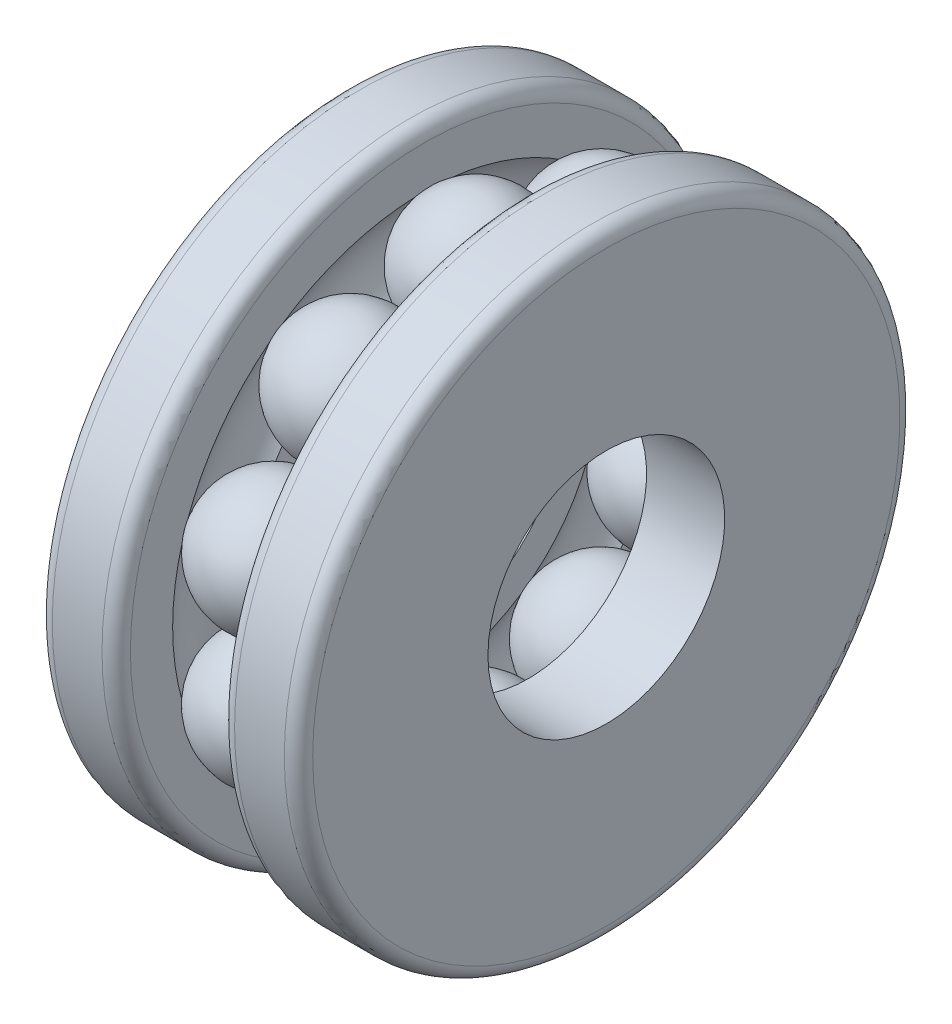
SolidWorks part; units mm, degrees
ref_plane "Front" through (0, 0, 0) normal (0, 0, 1) x (1, 0, 0)
ref_plane "Top" through (0, 0, 0) normal (0, 1, 0) x (1, 0, 0)
ref_plane "Right" through (0, 0, 0) normal (1, 0, 0) x (0, 0, -1)
sketch "Sketch1" plane through (0, 0, 0) normal (0, 0, 1) x (0, 1, 0)
  line L0 (0, 1.4099) -> (0, -1.5142) construction
  line L1 (6.25, 0) -> (11.75, 0)
  line L2 (4.3776, 0) -> (11.8663, 0) construction
  line L3 (9, 5.5) -> (13.0112, 5.5) construction
  line L4 (9, -5.5) -> (13.0112, -5.5) construction
  line L5 (5, 0) -> (5, 2.3607) construction
  line L6 (-5, 0) -> (-5, 2.3607) construction
  line L7 (13, 0) -> (13, 3.0588) construction
  line L8 (-13, 0) -> (-13, 3.0588) construction
  arc A0 (6.25, 0) -> (11.75, 0) centre (9, 0) ccw
  dimension "d0" = 5.5
  dimension "dd0" = 18
  dimension "T" = 11
  dimension "d" = 10
  dimension "DD" = 26
revolve "Revolve1" add sketch "Sketch1" angle 360 about L2
sketch "Sketch2" plane through (0, 0, 0) normal (0, 0, 1) x (0, 1, 0)
  line L0 (6, 5.5) -> (6, 2.2)
  line L1 (6, 2.2) -> (7.3836, 2.2)
  line L2 (6, 5.5) -> (13, 5.5)
  line L3 (13, 5.5) -> (13, 2.2)
  line L4 (13, 2.2) -> (10.6164, 2.2)
  line L5 (0, 4.8736) -> (0, -4.1797) construction
  line L6 (-8.0647, 0) -> (13.4529, 0) construction
  arc A0 (10.6164, 2.2) -> (7.3836, 2.2) centre (9, 0) ccw
  circle A1 centre (9, 0) radius 2.75 construction
  dimension "T" = 11
  dimension "dd1" = 5.46
  dimension "D" = 26
  dimension "d1" = 12
  dimension "B1/2" = 2.2
revolve "Revolve2" add sketch "Sketch2" angle 360 about L5
sketch "Sketch3" plane through (0, 0, 0) normal (0, 0, 1) x (0, 1, 0)
  line L0 (-2.5215, 0) -> (12.4263, 0) construction
  line L1 (5, -2.2) -> (7.3836, -2.2)
  line L2 (5, -2.2) -> (5, -5.5)
  line L3 (5, -5.5) -> (13, -5.5)
  line L4 (13, -2.2) -> (13, -5.5)
  line L5 (0, 8.7259) -> (0, -4.9884) construction
  line L6 (10.6164, -2.2) -> (13, -2.2)
  arc A0 (7.35, 2.2) -> (10.65, 2.2) centre (9, 0) ccw construction
  arc A1 (7.3836, -2.2) -> (10.6164, -2.2) centre (9, 0) ccw
  dimension "T" = 11
  dimension "d" = 10
  dimension "D1" = 5.46
  dimension "DD1" = 26
  dimension "D2" = 2.2
revolve "Revolve3" add sketch "Sketch3" angle 360 about L5
pattern_circular "Circular-Pattern1" count 10 over 360 about axis through (0, 0, 0) along (1, 0, 0) of "Revolve1"
fillet "Fillet1" radius 0.6 4 edges at (5.5, 0, 13) (2.2, 0, 13) (-2.2, 0, 13) (-5.5, 0, 13)
equation "\"d0@Sketch1\" = \"T@Sketch1\" / 2"
equation "\"dd0@Sketch1\" =  ( \"d@Sketch1\" + \"DD@Sketch1\" )  / 2"
equation "\"D@Sketch2\" = \"DD@Sketch1\""
equation "\"T@Sketch2\" = \"T@Sketch1\""
equation "\"dd1@Sketch2\" = \"d0@Sketch1\" - 0.04"
equation "\"B1/2@Sketch2\" = \"T@Sketch2\" / 5"
equation "\"d@Sketch3\" = \"d@Sketch1\""
equation "\"D2@Sketch3\" = \"B1/2@Sketch2\""
equation "\"D1@Sketch3\" = \"dd1@Sketch2\""
equation "\"T@Sketch3\" = \"T@Sketch2\""
equation "\"m@Circular-Pattern1\" = int( 3.14159265 / atn((  \"d0@Sketch1\"/ 2) / sqr( \"dd0@Sketch1\"/2 * \"dd0@Sketch1\"/2 - ( \"d0@Sketch1\"/ 2) *  ( \"d0@Sketch1\" / 2))))"
